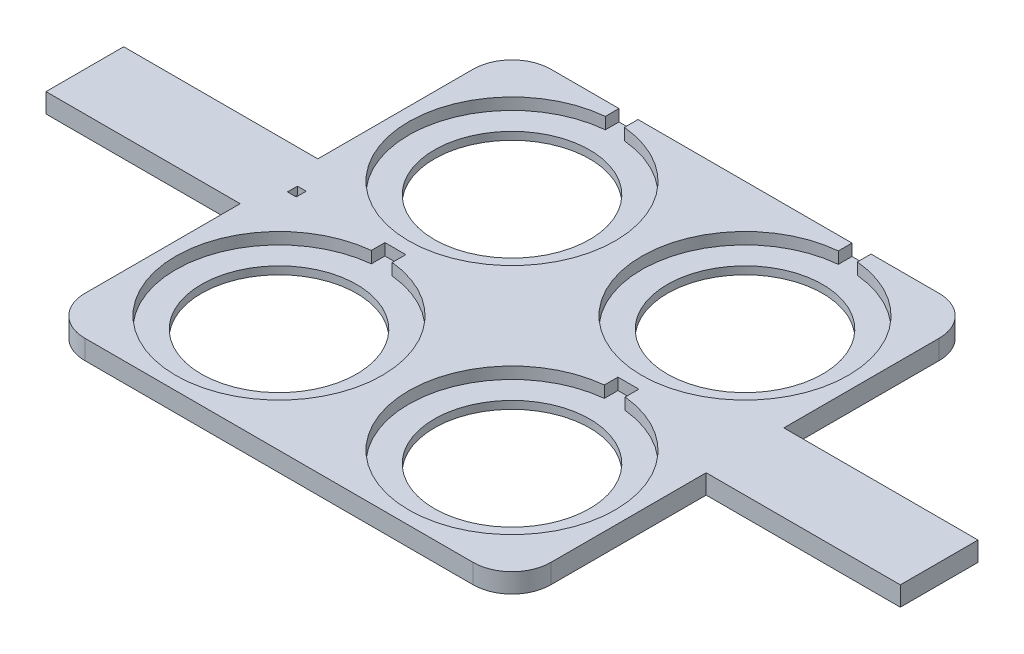
SolidWorks part; units mm, degrees
ref_plane "Front Plane" through (0, 0, 0) normal (0, 0, 1) x (1, 0, 0)
ref_plane "Top Plane" through (0, 0, 0) normal (0, 1, 0) x (1, 0, 0)
ref_plane "Right Plane" through (0, 0, 0) normal (1, 0, 0) x (0, 0, -1)
sketch "Sketch1" plane through (0, 0, 0) normal (0, 1, 0) x (1, 0, 0)
  line L1 (-60, 60) -> (60, 60)
  line L2 (-60, 60) -> (-60, -60)
  line L3 (-60, -60) -> (60, -60)
  line L4 (60, 60) -> (60, -60)
  line L5 (-60, 60) -> (60, -60) construction
  line L6 (-60, -60) -> (60, 60) construction
  point P0 (0, 0)
  dimension "D1" = 120
  dimension "D2" = 120
extrude "Boss-Extrude1" add sketch "Sketch1" along normal blind 5
sketch "Sketch2" plane through (0, 5, 0) normal (0, 1, 0) x (1, 0, 0)
  circle A0 centre (-30, 30) radius 20
  circle A2 centre (30, 30) radius 20
  circle A3 centre (30, -30) radius 20
  circle A4 centre (-30, -30) radius 20
  circle A5 centre (-30, 30) radius 26.6
  circle A6 centre (30, 30) radius 26.6
  circle A7 centre (30, -30) radius 26.6
  circle A8 centre (-30, -30) radius 26.6
  point P22 (0, 0)
  point P30 (0, 0)
  dimension "D1" = 40
  dimension "D3" = 53.2
  dimension "D2" = 4
  dimension "D4" = 4
extrude "Cut-Extrude4" cut sketch "Sketch2" against normal blind 5 contours A2 | A4 | A3 | A0
sketch "Sketch3" plane through (0, 5, 0) normal (0, 1, 0) x (1, 0, 0)
  circle A2 centre (-30, 30) radius 26.6
  circle A3 centre (30, 30) radius 26.6
  circle A4 centre (30, -30) radius 26.6
  circle A5 centre (-30, -30) radius 26.6
  point P16 (0, 0)
  circle M5 centre (30, -30) radius 20
  circle M6 centre (-30, -30) radius 20
  circle M7 centre (30, 30) radius 20
  dimension "D1" = 53.2
  dimension "D2" = 4
extrude "Cut-Extrude5" cut sketch "Sketch3" against normal blind 3 contours A3 M7 | A5 M6 | A4 M5 | A2
sketch "Sketch4" plane through (60, 0, 0) normal (1, 0, 0) x (0, 0, -1)
  line L0 (0, 0) -> (0, 5) construction
  line L1 (-60, 5) -> (60, 5) construction
  line L2 (-60, 0) -> (60, 0) construction
  line L3 (-30, 5) -> (30, 5)
  line L4 (-30, 5) -> (-30, 0)
  line L5 (-30, 0) -> (30, 0)
  line L6 (30, 5) -> (30, 0)
  line L7 (-30, 5) -> (30, 0) construction
  line L8 (-30, 0) -> (30, 5) construction
  point P5 (0, 2.5)
  dimension "D1" = 60
extrude "Boss-Extrude2" add sketch "Sketch4" along normal blind 50 contours L4 L3 L6 L5
sketch "Sketch5" plane through (-60, 0, 0) normal (-1, 0, 0) x (0, 0, 1)
  line L0 (0, 0) -> (0, 5) construction
  line L1 (-60, 5) -> (60, 5) construction
  line L2 (-60, 0) -> (60, 0) construction
  line L3 (-30, 5) -> (30, 5)
  line L4 (-30, 5) -> (-30, 0)
  line L5 (-30, 0) -> (30, 0)
  line L6 (30, 5) -> (30, 0)
  line L7 (-30, 5) -> (30, 0) construction
  line L8 (-30, 0) -> (30, 5) construction
  point P5 (0, 2.5)
  dimension "D1" = 60
extrude "Boss-Extrude3" add sketch "Sketch5" along normal blind 50
sketch "Sketch6" plane through (0, 5, 0) normal (0, 1, 0) x (1, 0, 0)
  line L1 (-110, 30) -> (-60, 30)
  line L2 (-110, 30) -> (-110, -30)
  line L3 (-110, -30) -> (-60, -30)
  line L4 (-60, 30) -> (-60, -30)
fillet "Fillet3" radius 10 1 edges at (-60, 2.5, 60)
fillet "Fillet4" radius 10 1 edges at (60, 2.5, 60)
fillet "Fillet5" radius 10 1 edges at (-60, 2.5, -60)
fillet "Fillet6" radius 10 1 edges at (60, 2.5, -60)
sketch "Sketch8" plane through (0, 5, 0) normal (0, 1, 0) x (1, 0, 0)
  line L2 (-60, 30) -> (-60, -30) construction
  line L3 (-110, 30) -> (-60, 30)
  line L4 (-110, 30) -> (-110, 10)
  line L5 (-110, 10) -> (-60, 10)
  line L6 (-60, 30) -> (-60, 10)
  line L7 (-110, 0) -> (110, 0) construction
  line L8 (-110, 30) -> (-110, -30) construction
  line L9 (110, -30) -> (110, 30) construction
  line L10 (-110, -10) -> (-60, -10)
  line L11 (-60, -30) -> (-60, -10)
  line L12 (-110, -30) -> (-60, -30)
  line L13 (-110, -30) -> (-110, -10)
  line L14 (0, 60) -> (0, -60) construction
  line L15 (50, 60) -> (-50, 60) construction
  line L16 (-50, -60) -> (50, -60) construction
  line L17 (110, -30) -> (110, -10)
  line L18 (110, -30) -> (60, -30)
  line L19 (60, -30) -> (60, -10)
  line L20 (110, -10) -> (60, -10)
  line L21 (110, 10) -> (60, 10)
  line L22 (60, 30) -> (60, 10)
  line L23 (110, 30) -> (60, 30)
  line L24 (110, 30) -> (110, 10)
  dimension "D1" = 20
extrude "Cut-Extrude6" cut sketch "Sketch8" against normal blind 10
sketch "Sketch10" plane through (0, 5, 0) normal (0, 1, 0) x (1, 0, 0)
  line L0 (0, 0) -> (-55.4064, 0) construction
  line L1 (-55.4064, -22.1211) -> (-55.4064, 0) construction
  line L3 (-56.5369, -1.2871) -> (-54.2758, -1.2871)
  line L4 (-56.5369, -1.2871) -> (-56.5369, 1.2871)
  line L5 (-56.5369, 1.2871) -> (-54.2758, 1.2871)
  line L6 (-54.2758, -1.2871) -> (-54.2758, 1.2871)
  line L7 (-56.5369, -1.2871) -> (-54.2758, 1.2871) construction
  line L8 (-56.5369, 1.2871) -> (-54.2758, -1.2871) construction
  circle A0 centre (-30, -30) radius 26.6 construction
  circle A1 centre (-30, -30) radius 26.6 construction
extrude "Cut-Extrude7" cut sketch "Sketch10" against normal blind 2
sketch "Sketch12" plane through (0, 5, 0) normal (0, 1, 0) x (1, 0, 0)
  line L0 (0, 60) -> (0, -60) construction
  line L1 (-32.6888, -0.0316) -> (-27.3112, -0.0316)
  line L2 (-32.6888, -0.0316) -> (-32.6888, -6.7684)
  line L3 (-32.6888, -6.7684) -> (-27.3112, -6.7684)
  line L4 (-27.3112, -0.0316) -> (-27.3112, -6.7684)
  line L5 (-32.6888, -0.0316) -> (-27.3112, -6.7684) construction
  line L6 (-32.6888, -6.7684) -> (-27.3112, -0.0316) construction
  line L7 (50, 60) -> (-50, 60) construction
  line L8 (-50, -60) -> (50, -60) construction
  line L9 (32.6888, -6.7684) -> (27.3112, -6.7684)
  line L10 (27.3112, -0.0316) -> (27.3112, -6.7684)
  line L11 (32.6888, -0.0316) -> (27.3112, -0.0316)
  line L12 (32.6888, -0.0316) -> (32.6888, -6.7684)
  circle A0 centre (-30, -30) radius 26.6 construction
  circle A1 centre (-30, -30) radius 26.6 construction
  point P0 (-30, -3.4)
extrude "Cut-Extrude10" cut sketch "Sketch12" against normal blind 3
sketch "Sketch14" plane through (0, 5, 0) normal (0, 1, 0) x (1, 0, 0)
  line L0 (-30, 56.6) -> (-30, 30) construction
  line L1 (0, 0) -> (0, 60) construction
  line L2 (-32.4513, 60.1213) -> (-27.5487, 60.1213)
  line L3 (-32.4513, 60.1213) -> (-32.4513, 53.0787)
  line L4 (-32.4513, 53.0787) -> (-27.5487, 53.0787)
  line L5 (-27.5487, 60.1213) -> (-27.5487, 53.0787)
  line L6 (-32.4513, 60.1213) -> (-27.5487, 53.0787) construction
  line L7 (-32.4513, 53.0787) -> (-27.5487, 60.1213) construction
  line L8 (50, 60) -> (-50, 60) construction
  line L9 (32.4513, 53.0787) -> (27.5487, 53.0787)
  line L10 (27.5487, 60.1213) -> (27.5487, 53.0787)
  line L11 (32.4513, 60.1213) -> (27.5487, 60.1213)
  line L12 (32.4513, 60.1213) -> (32.4513, 53.0787)
  circle A0 centre (-30, 30) radius 26.6 construction
  circle A1 centre (-30, 30) radius 26.6 construction
extrude "Cut-Extrude11" cut sketch "Sketch14" against normal blind 3
